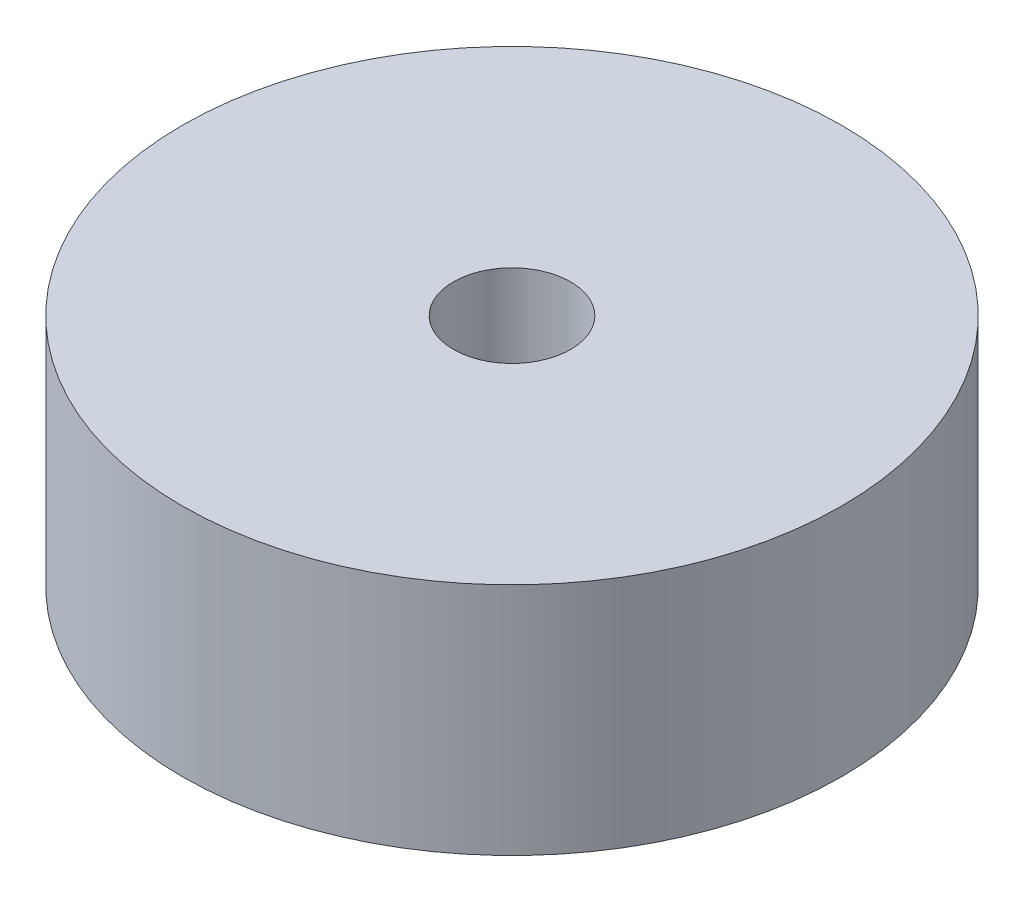
SolidWorks part; units mm, degrees
ref_plane "Front Plane" through (0, 0, 0) normal (0, 0, 1) x (1, 0, 0)
ref_plane "Top Plane" through (0, 0, 0) normal (0, 1, 0) x (1, 0, 0)
ref_plane "Right Plane" through (0, 0, 0) normal (1, 0, 0) x (0, 0, -1)
sketch "Sketch1" plane through (0, 0, 0) normal (0, 1, 0) x (1, 0, 0)
  circle A0 centre (0, 0) radius 4
  circle A1 centre (0, 0) radius 22.5
  dimension "D1" = 8
  dimension "D2" = 45
extrude "Boss-Extrude1" add sketch "Sketch1" along normal blind 16
